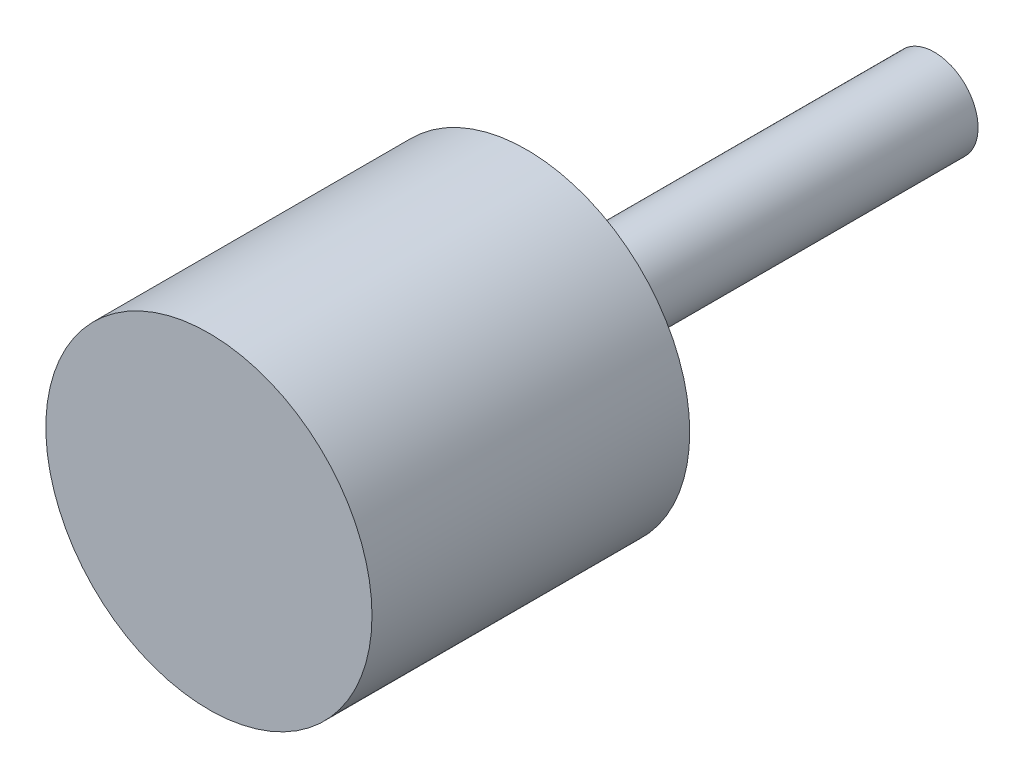
SolidWorks part; units mm, degrees
ref_plane "Front" through (0, 0, 0) normal (0, 0, 1) x (1, 0, 0)
ref_plane "Top" through (0, 0, 0) normal (0, 1, 0) x (1, 0, 0)
ref_plane "Right" through (0, 0, 0) normal (1, 0, 0) x (0, 0, -1)
sketch "Sketch1" plane through (0, 0, 0) normal (0, 0, 1) x (1, 0, 0)
  circle A0 centre (0, 0) radius 3.11
extrude "Extrude1" add sketch "Sketch1" along normal blind 29
sketch "Sketch2" plane through (0, 0, 29) normal (0, 0, 1) x (1, 0, 0)
  circle A0 centre (0, 0) radius 11.6
extrude "Extrude2" add sketch "Sketch2" along normal blind 22.6
